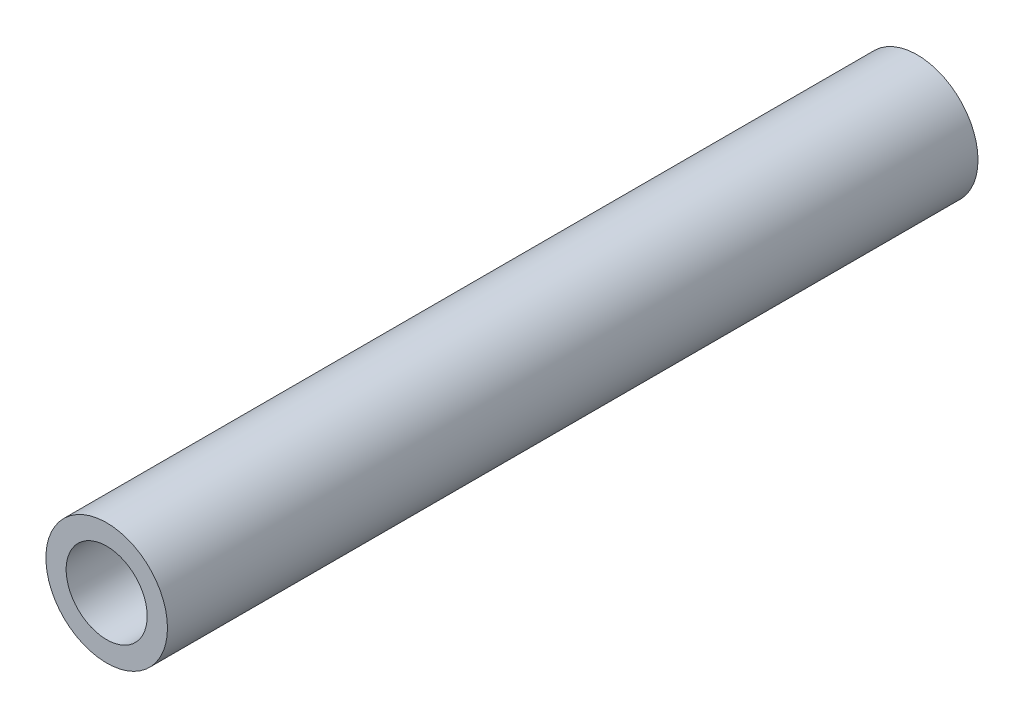
SolidWorks part; units mm, degrees
ref_plane "前视基准面" through (0, 0, 0) normal (0, 0, 1) x (1, 0, 0)
ref_plane "上视基准面" through (0, 0, 0) normal (0, 1, 0) x (1, 0, 0)
ref_plane "右视基准面" through (0, 0, 0) normal (1, 0, 0) x (0, 0, -1)
sketch "草图1" plane through (0, 0, 0) normal (0, 0, 1) x (1, 0, 0)
  circle A0 centre (0, 0) radius 3
  circle A1 centre (0, 0) radius 2
  dimension "D1" = 4
  dimension "D2" = 6
extrude "凸台-拉伸1" add sketch "草图1" along normal mid plane 40
